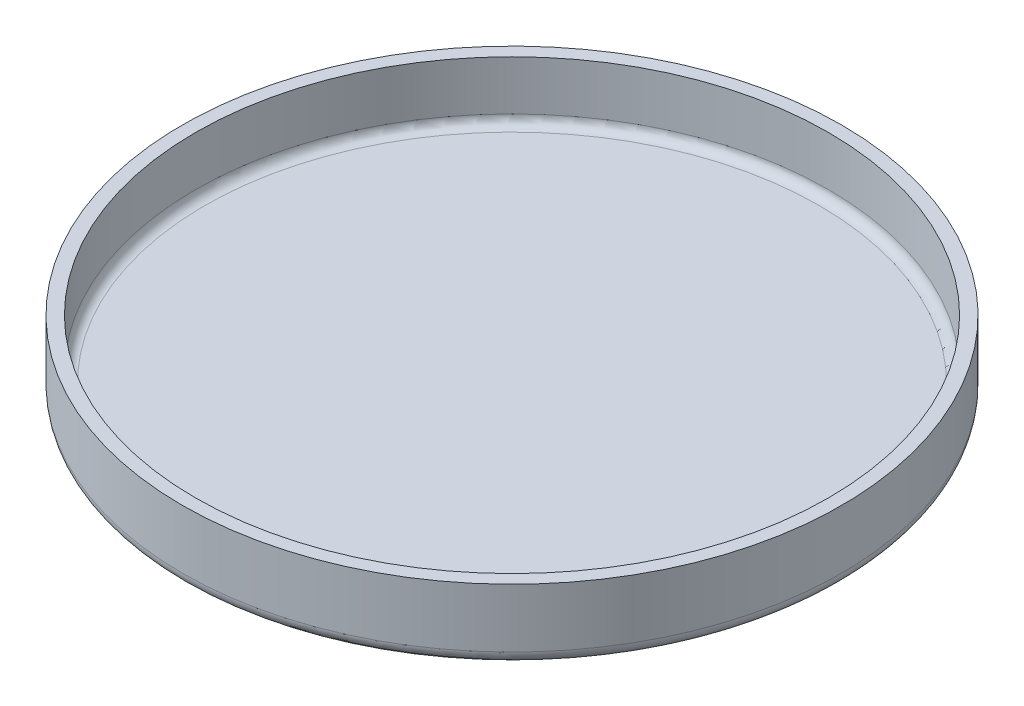
SolidWorks part; units mm, degrees
ref_plane "Alzado" through (0, 0, 0) normal (0, 0, 1) x (1, 0, 0)
ref_plane "Planta" through (0, 0, 0) normal (0, 1, 0) x (1, 0, 0)
ref_plane "Vista lateral" through (0, 0, 0) normal (1, 0, 0) x (0, 0, -1)
sketch "Croquis1" plane through (0, 0, 0) normal (0, 0, 1) x (1, 0, 0)
  line L0 (0, 0) -> (0, 45.5013) construction
  line L1 (48.5, 0) -> (0, 0)
  line L2 (0, 0) -> (0, 2)
  line L3 (0, 2) -> (47.0858, 2)
  line L6 (50.5, 2) -> (50.5, 11)
  line L7 (50.5, 11) -> (48.5, 11)
  line L8 (48.5, 3.4142) -> (48.5, 11)
  arc A0 (48.5, 3.4142) -> (47.0858, 2) centre (47.0858, 3.4142) cw
  arc A1 (50.5, 2) -> (48.5, 0) centre (48.5, 2) cw
  point P12 (50.5, 0)
  dimension "D6" = 2
  dimension "D1" = 2
  dimension "D3" = 50.5
  dimension "D4" = 11
revolve "Revolución1" add sketch "Croquis1" angle 360 about L0
